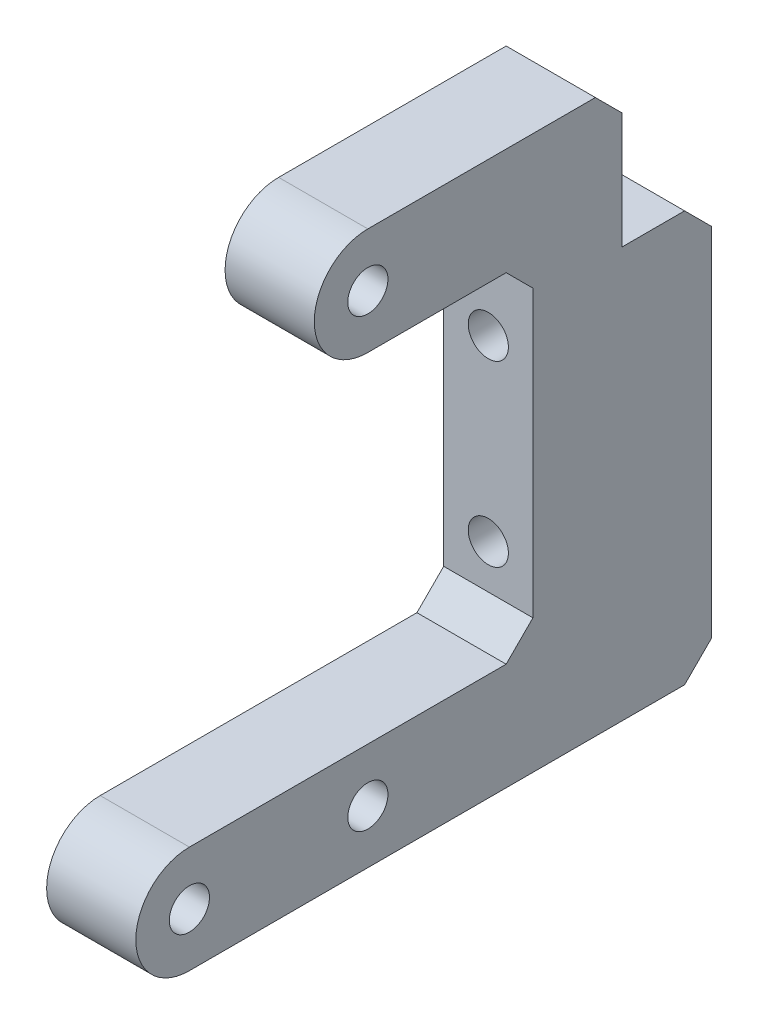
SolidWorks part; units mm, degrees
material "3D printed plastic"
ref_plane "Front Plane" through (0, 0, 0) normal (0, 0, 1) x (1, 0, 0)
ref_plane "Top Plane" through (0, 0, 0) normal (0, 1, 0) x (1, 0, 0)
ref_plane "Right Plane" through (0, 0, 0) normal (1, 0, 0) x (0, 0, -1)
sketch "Sketch1" plane through (0, 0, 0) normal (1, 0, 0) x (0, 0, -1)
  line L0 (-20, -50) -> (0, -50) construction
  line L1 (0, -50) -> (0, 0) construction
  line L2 (-20, -56) -> (38.5, -56)
  line L3 (38.5, -56) -> (38.5, 6)
  line L4 (38.5, 6) -> (0, 6)
  line L5 (0, -6) -> (18.5, -6)
  line L6 (18.5, -6) -> (18.5, -44)
  line L7 (18.5, -44) -> (-20, -44)
  circle A0 centre (0, 0) radius 2.25
  circle A1 centre (0, -50) radius 2.25
  circle A2 centre (-20, -50) radius 2.25
  arc A3 (0, 6) -> (0, -6) centre (0, 0) ccw
  arc A4 (-20, -44) -> (-20, -56) centre (-20, -50) ccw
  dimension "D1" = 50
  dimension "D3" = 4.5
  dimension "D4" = 12
  dimension "D2" = 20
  dimension "D5" = 38.5
  dimension "D6" = 20
extrude "Boss-Extrude1" add sketch "Sketch1" along normal mid plane 10
sketch "Sketch2" plane through (0, 0, -18.5) normal (0, 0, 1) x (1, 0, 0)
  line L0 (0, -36.1) -> (0, -16.1) construction
  line L1 (0, -16.1) -> (0, 0) construction
  circle A0 centre (0, -16.1) radius 2.25
  circle A1 centre (0, -36.1) radius 2.25
  dimension "D1" = 20
  dimension "D2" = 4.5
  dimension "D3" = 16.1
extrude "Cut-Extrude1" cut sketch "Sketch2" against normal through all
sketch "Sketch3" plane through (5, 0, 0) normal (1, 0, 0) x (0, 0, -1)
  line L1 (38.5, 6) -> (28.5, 6)
  line L2 (38.5, 6) -> (38.5, -10)
  line L3 (38.5, -10) -> (28.5, -10)
  line L4 (28.5, 6) -> (28.5, -10)
  dimension "D1" = 10
  dimension "D2" = 16
extrude "Cut-Extrude2" cut sketch "Sketch3" against normal through all
chamfer "Chamfer1" distance 3 angle 45 5 edges at (0, -56, -38.5) (0, -44, -18.5) (0, -6, -18.5) (0, -10, -38.5) (0, 6, -28.5)
